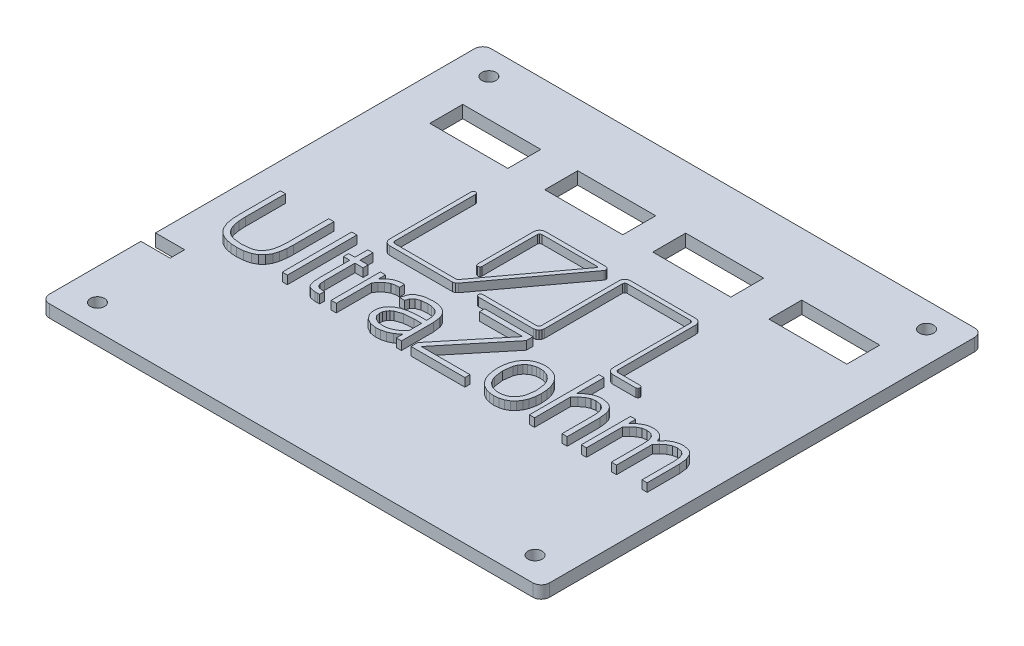
SolidWorks part; units mm, degrees
ref_plane "Ebene vorne" through (0, 0, 0) normal (0, 0, 1) x (1, 0, 0)
ref_plane "Ebene oben" through (0, 0, 0) normal (0, 1, 0) x (1, 0, 0)
ref_plane "Ebene rechts" through (0, 0, 0) normal (1, 0, 0) x (0, 0, -1)
sketch "Skizze1" plane through (0, 0, 0) normal (0, 1, 0) x (1, 0, 0)
  line L1 (-58, -53) -> (58, -53)
  line L2 (-60, -51) -> (-60, 51)
  line L3 (-58, 53) -> (58, 53)
  line L4 (60, -51) -> (60, 51)
  line L5 (-60, -53) -> (60, 53) construction
  line L6 (-60, 53) -> (60, -53) construction
  arc A0 (58, -53) -> (60, -51) centre (58, -51) ccw
  arc A1 (58, 53) -> (60, 51) centre (58, 51) cw
  arc A2 (-60, 51) -> (-58, 53) centre (-58, 51) cw
  arc A3 (-58, -53) -> (-60, -51) centre (-58, -51) cw
  point P0 (0, 0)
  dimension "D3" = 2
  dimension "D1" = 120
  dimension "D2" = 106
extrude "Aufsatz-Linear austragen1" add sketch "Skizze1" along normal blind 3
sketch "Skizze2" plane through (0, 3, 0) normal (0, 1, 0) x (1, 0, 0)
  line L1 (52.5, 46.97) -> (-52.5, 46.97) construction
  line L2 (52.5, 46.97) -> (52.5, -46.97) construction
  line L3 (52.5, -46.97) -> (-52.5, -46.97) construction
  line L4 (-52.5, 46.97) -> (-52.5, -46.97) construction
  line L5 (52.5, 46.97) -> (-52.5, -46.97) construction
  line L6 (52.5, -46.97) -> (-52.5, 46.97) construction
  circle A0 centre (-52.5, 46.97) radius 1.7
  circle A1 centre (52.5, 46.97) radius 1.7
  circle A2 centre (52.5, -46.97) radius 1.7
  circle A3 centre (-52.5, -46.97) radius 1.7
  point P0 (0, 0)
  dimension "D3" = 3.4
  dimension "D1" = 93.94
  dimension "D2" = 105
  dimension "D4" = 2
  dimension "D5" = 2
extrude "Schnitt-Linear austragen1" cut sketch "Skizze2" against normal blind 3
sketch "Skizze3" plane through (0, 3, 0) normal (0, 1, 0) x (1, 0, 0)
  line L0 (60, -51) -> (60, 51) construction
  line L1 (31.5, 30.13) -> (50.22, 30.13)
  line L2 (31.5, 30.13) -> (31.5, 38.03)
  line L3 (31.5, 38.03) -> (50.22, 38.03)
  line L4 (50.22, 30.13) -> (50.22, 38.03)
  line L5 (31.5, 30.13) -> (50.22, 38.03) construction
  line L6 (31.5, 38.03) -> (50.22, 30.13) construction
  line L7 (58, 53) -> (-58, 53) construction
  point P0 (40.86, 34.08)
  dimension "D1" = 9.78
  dimension "D2" = 18.72
  dimension "D3" = 7.9
  dimension "D4" = 14.97
extrude "Schnitt-Linear austragen2" cut sketch "Skizze3" against normal blind 3
pattern_linear "Lineares Muster1" count 2 spacing 27.85 along (-1, 0, 0) of "Schnitt-Linear austragen2"
pattern_linear "Lineares Muster2" count 2 spacing 53.76 along (-1, 0, 0) of "Schnitt-Linear austragen2"
pattern_linear "Lineares Muster3" count 2 spacing 81.35 along (-1, 0, 0) of "Schnitt-Linear austragen2"
sketch "Skizze4" plane through (0, 3, 0) normal (0, 1, 0) x (1, 0, 0)
  line L0 (-60, 51) -> (-60, -51) construction
  line L1 (-60, -29.05) -> (-53, -29.05)
  line L2 (-60, -29.05) -> (-60, -25.55)
  line L3 (-60, -25.55) -> (-53, -25.55)
  line L4 (-53, -29.05) -> (-53, -25.55)
  line L5 (-53, -27.3) -> (-60, -27.3) construction
  line L6 (-58, -53) -> (58, -53) construction
  dimension "D1" = 25.7
  dimension "D2" = 3.5
  dimension "D3" = 7
extrude "Schnitt-Linear austragen3" cut sketch "Skizze4" against normal blind 3
sketch "Skizze9" plane through (0, 3, 0) normal (0, 1, 0) x (1, 0, 0)
  line L0 (-12.1482, -2.1288) -> (-27.2801, -2.1288)
  line L1 (-27.2801, -2.1288) -> (-27.8105, -2.0208)
  line L2 (-27.8105, -2.0208) -> (-28.2435, -1.7282)
  line L3 (-28.2435, -1.7282) -> (-28.5353, -1.2947)
  line L4 (-28.5353, -1.2947) -> (-28.6423, -0.7641)
  line L5 (-28.6423, -0.7641) -> (-28.6423, 18.8843)
  line L6 (-28.6423, 18.8843) -> (-28.4902, 19.2514)
  line L7 (-28.4902, 19.2514) -> (-28.1231, 19.4035)
  line L8 (-28.1231, 19.4035) -> (-27.7576, 19.2505)
  line L9 (-27.7576, 19.2505) -> (-27.6065, 18.8843)
  line L10 (-27.6065, 18.8843) -> (-27.6065, -0.5614)
  line L11 (-27.6065, -0.5614) -> (-27.4542, -0.9276)
  line L12 (-27.4542, -0.9276) -> (-27.0873, -1.0781)
  line L13 (-27.0873, -1.0781) -> (-12.1482, -1.0781)
  line L14 (-12.1482, -1.0781) -> (-12.0395, -1.0212)
  line L15 (-12.0395, -1.0212) -> (2.1901, 18.2613)
  line L16 (2.1901, 18.2613) -> (2.2024, 18.4049)
  line L17 (2.2024, 18.4049) -> (2.0788, 18.4789)
  line L18 (2.0788, 18.4789) -> (-11.3374, 18.4789)
  line L19 (-11.3374, 18.4789) -> (-11.7045, 18.3268)
  line L20 (-11.7045, 18.3268) -> (-11.8565, 17.9597)
  line L21 (-11.8565, 17.9597) -> (-11.8565, 4.6399)
  line L22 (-11.8565, 4.6399) -> (-12.007, 4.273)
  line L23 (-12.007, 4.273) -> (-12.3732, 4.1208)
  line L24 (-12.3732, 4.1208) -> (-12.7403, 4.2728)
  line L25 (-12.7403, 4.2728) -> (-12.8924, 4.6399)
  line L26 (-12.8924, 4.6399) -> (-12.8924, 18.1427)
  line L27 (-12.8924, 18.1427) -> (-12.7853, 18.6729)
  line L28 (-12.7853, 18.6729) -> (-12.4934, 19.1059)
  line L29 (-12.4934, 19.1059) -> (-12.0604, 19.3978)
  line L30 (-12.0604, 19.3978) -> (-11.5302, 19.5048)
  line L31 (-11.5302, 19.5048) -> (3.0553, 19.5048)
  line L32 (3.0553, 19.5048) -> (3.4265, 19.4185)
  line L33 (3.4265, 19.4185) -> (3.6887, 19.1421)
  line L34 (3.6887, 19.1421) -> (3.7552, 18.7669)
  line L35 (3.7552, 18.7669) -> (3.6041, 18.4171)
  line L36 (3.6041, 18.4171) -> (-11.2113, -1.6343)
  line L37 (-11.2113, -1.6343) -> (-11.6241, -1.987)
  line L38 (-11.6241, -1.987) -> (-12.1482, -2.1288)
  line L39 (-12.1482, -2.1288) -> (-12.1482, -2.1288)
  line L40 (31.8284, -2.1288) -> (26.281, -2.1288)
  line L41 (26.281, -2.1288) -> (25.7506, -2.0208)
  line L42 (25.7506, -2.0208) -> (25.3176, -1.7282)
  line L43 (25.3176, -1.7282) -> (25.0258, -1.2947)
  line L44 (25.0258, -1.2947) -> (24.9188, -0.7641)
  line L45 (24.9188, -0.7641) -> (24.9188, 17.9523)
  line L46 (24.9188, 17.9523) -> (24.7676, 18.3185)
  line L47 (24.7676, 18.3185) -> (24.4021, 18.4715)
  line L48 (24.4021, 18.4715) -> (9.1096, 18.4715)
  line L49 (9.1096, 18.4715) -> (8.7441, 18.3185)
  line L50 (8.7441, 18.3185) -> (8.5929, 17.9523)
  line L51 (8.5929, 17.9523) -> (8.5929, -0.7518)
  line L52 (8.5929, -0.7518) -> (8.4931, -1.2767)
  line L53 (8.4931, -1.2767) -> (8.1994, -1.723)
  line L54 (8.1994, -1.723) -> (7.7568, -2.0223)
  line L55 (7.7568, -2.0223) -> (7.2332, -2.1288)
  line L56 (7.2332, -2.1288) -> (-5.9605, -2.1288)
  line L57 (-5.9605, -2.1288) -> (-6.3276, -1.9767)
  line L58 (-6.3276, -1.9767) -> (-6.4797, -1.6096)
  line L59 (-6.4797, -1.6096) -> (-6.3276, -1.2425)
  line L60 (-6.3276, -1.2425) -> (-5.9605, -1.0905)
  line L61 (-5.9605, -1.0905) -> (7.0379, -1.0905)
  line L62 (7.0379, -1.0905) -> (7.4049, -0.94)
  line L63 (7.4049, -0.94) -> (7.5571, -0.5738)
  line L64 (7.5571, -0.5738) -> (7.5571, 18.1427)
  line L65 (7.5571, 18.1427) -> (7.6608, 18.664)
  line L66 (7.6608, 18.664) -> (7.956, 19.1059)
  line L67 (7.956, 19.1059) -> (8.3979, 19.4011)
  line L68 (8.3979, 19.4011) -> (8.9192, 19.5048)
  line L69 (8.9192, 19.5048) -> (24.5925, 19.5048)
  line L70 (24.5925, 19.5048) -> (25.1138, 19.4011)
  line L71 (25.1138, 19.4011) -> (25.5557, 19.1059)
  line L72 (25.5557, 19.1059) -> (25.851, 18.664)
  line L73 (25.851, 18.664) -> (25.9546, 18.1427)
  line L74 (25.9546, 18.1427) -> (25.9546, -0.5639)
  line L75 (25.9546, -0.5639) -> (26.1068, -0.9301)
  line L76 (26.1068, -0.9301) -> (26.4738, -1.0806)
  line L77 (26.4738, -1.0806) -> (31.8284, -1.0806)
  line L78 (31.8284, -1.0806) -> (32.1939, -1.2335)
  line L79 (32.1939, -1.2335) -> (32.3451, -1.5997)
  line L80 (32.3451, -1.5997) -> (32.1974, -1.9723)
  line L81 (32.1974, -1.9723) -> (31.8284, -2.1288)
  line L82 (-45.3538, -20.7933) -> (-46.6503, -20.7279)
  line L83 (-46.6503, -20.7279) -> (-47.9249, -20.4818)
  line L84 (-47.9249, -20.4818) -> (-48.8507, -20.1396)
  line L85 (-48.8507, -20.1396) -> (-49.6998, -19.6364)
  line L86 (-49.6998, -19.6364) -> (-50.323, -19.0688)
  line L87 (-50.323, -19.0688) -> (-50.8197, -18.3879)
  line L88 (-50.8197, -18.3879) -> (-51.4501, -16.8651)
  line L89 (-51.4501, -16.8651) -> (-51.7196, -15.189)
  line L90 (-51.7196, -15.189) -> (-51.774, -13.4981)
  line L91 (-51.774, -13.4981) -> (-51.774, -3.8098)
  line L92 (-51.774, -3.8098) -> (-50.5379, -3.8098)
  line L93 (-50.5379, -3.8098) -> (-50.5379, -13.4511)
  line L94 (-50.5379, -13.4511) -> (-50.4708, -15.013)
  line L95 (-50.4708, -15.013) -> (-50.1918, -16.5511)
  line L96 (-50.1918, -16.5511) -> (-49.8031, -17.5485)
  line L97 (-49.8031, -17.5485) -> (-49.1782, -18.4176)
  line L98 (-49.1782, -18.4176) -> (-48.4265, -18.987)
  line L99 (-48.4265, -18.987) -> (-47.5491, -19.3323)
  line L100 (-47.5491, -19.3323) -> (-45.3464, -19.5795)
  line L101 (-45.3464, -19.5795) -> (-43.1215, -19.3323)
  line L102 (-43.1215, -19.3323) -> (-42.2409, -18.988)
  line L103 (-42.2409, -18.988) -> (-41.4924, -18.4102)
  line L104 (-41.4924, -18.4102) -> (-40.883, -17.5379)
  line L105 (-40.883, -17.5379) -> (-40.5035, -16.5437)
  line L106 (-40.5035, -16.5437) -> (-40.2315, -15.0087)
  line L107 (-40.2315, -15.0087) -> (-40.1673, -13.4511)
  line L108 (-40.1673, -13.4511) -> (-40.1673, -3.8098)
  line L109 (-40.1673, -3.8098) -> (-38.9313, -3.8098)
  line L110 (-38.9313, -3.8098) -> (-38.9313, -13.5005)
  line L111 (-38.9313, -13.5005) -> (-38.9957, -15.0459)
  line L112 (-38.9957, -15.0459) -> (-39.223, -16.5759)
  line L113 (-39.223, -16.5759) -> (-39.6001, -17.7802)
  line L114 (-39.6001, -17.7802) -> (-40.2365, -18.87)
  line L115 (-40.2365, -18.87) -> (-41.1247, -19.7201)
  line L116 (-41.1247, -19.7201) -> (-42.2093, -20.2989)
  line L117 (-42.2093, -20.2989) -> (-43.7585, -20.6926)
  line L118 (-43.7585, -20.6926) -> (-45.3538, -20.7933)
  line L119 (-33.4036, -20.4892) -> (-34.6396, -20.4892)
  line L120 (-34.6396, -20.4892) -> (-34.6396, -3.8098)
  line L121 (-34.6396, -3.8098) -> (-33.4036, -3.8098)
  line L122 (-33.4036, -3.8098) -> (-33.4036, -20.4892)
  line L123 (-25.5398, -20.5955) -> (-26.0614, -20.6425)
  line L124 (-26.0614, -20.6425) -> (-26.583, -20.6573)
  line L125 (-26.583, -20.6573) -> (-27.866, -20.4349)
  line L126 (-27.866, -20.4349) -> (-28.2913, -20.1646)
  line L127 (-28.2913, -20.1646) -> (-28.6077, -19.7723)
  line L128 (-28.6077, -19.7723) -> (-28.9389, -18.6698)
  line L129 (-28.9389, -18.6698) -> (-29.0156, -17.1222)
  line L130 (-29.0156, -17.1222) -> (-29.0156, -9.9036)
  line L131 (-29.0156, -9.9036) -> (-30.5359, -9.9036)
  line L132 (-30.5359, -9.9036) -> (-30.5359, -8.6848)
  line L133 (-30.5359, -8.6848) -> (-29.0156, -8.6848)
  line L134 (-29.0156, -8.6848) -> (-29.0156, -5.5897)
  line L135 (-29.0156, -5.5897) -> (-27.7795, -5.5897)
  line L136 (-27.7795, -5.5897) -> (-27.7795, -8.6824)
  line L137 (-27.7795, -8.6824) -> (-25.829, -8.6824)
  line L138 (-25.829, -8.6824) -> (-25.829, -9.9011)
  line L139 (-25.829, -9.9011) -> (-27.7795, -9.9011)
  line L140 (-27.7795, -9.9011) -> (-27.7795, -17.226)
  line L141 (-27.7795, -17.226) -> (-27.6707, -18.3929)
  line L142 (-27.6707, -18.3929) -> (-27.3494, -19.0628)
  line L143 (-27.3494, -19.0628) -> (-26.8203, -19.3669)
  line L144 (-26.8203, -19.3669) -> (-26.1059, -19.4361)
  line L145 (-26.1059, -19.4361) -> (-25.8142, -19.4361)
  line L146 (-25.8142, -19.4361) -> (-25.5373, -19.4213)
  line L147 (-25.5373, -19.4213) -> (-25.5398, -20.5955)
  line L148 (-17.4139, -9.6292) -> (-17.7822, -9.5995)
  line L149 (-17.7822, -9.5995) -> (-18.2297, -9.5995)
  line L150 (-18.2297, -9.5995) -> (-19.2457, -9.8121)
  line L151 (-19.2457, -9.8121) -> (-20.1827, -10.3684)
  line L152 (-20.1827, -10.3684) -> (-21.0108, -11.1446)
  line L153 (-21.0108, -11.1446) -> (-21.6709, -12.0346)
  line L154 (-21.6709, -12.0346) -> (-21.6709, -20.4892)
  line L155 (-21.6709, -20.4892) -> (-22.9069, -20.4892)
  line L156 (-22.9069, -20.4892) -> (-22.9069, -8.6848)
  line L157 (-22.9069, -8.6848) -> (-21.6709, -8.6848)
  line L158 (-21.6709, -8.6848) -> (-21.6709, -10.314)
  line L159 (-21.6709, -10.314) -> (-20.6351, -9.3251)
  line L160 (-20.6351, -9.3251) -> (-19.6462, -8.7293)
  line L161 (-19.6462, -8.7293) -> (-18.7167, -8.4475)
  line L162 (-18.7167, -8.4475) -> (-17.9034, -8.3808)
  line L163 (-17.9034, -8.3808) -> (-17.6734, -8.3808)
  line L164 (-17.6734, -8.3808) -> (-17.4262, -8.403)
  line L165 (-17.4262, -8.403) -> (-17.4139, -9.6292)
  line L166 (-7.2782, -18.9664) -> (-8.5142, -19.8712)
  line L167 (-8.5142, -19.8712) -> (-9.6885, -20.4349)
  line L168 (-9.6885, -20.4349) -> (-10.8331, -20.7167)
  line L169 (-10.8331, -20.7167) -> (-11.9851, -20.7933)
  line L170 (-11.9851, -20.7933) -> (-13.4436, -20.5585)
  line L171 (-13.4436, -20.5585) -> (-14.6105, -19.8885)
  line L172 (-14.6105, -19.8885) -> (-15.3867, -18.8354)
  line L173 (-15.3867, -18.8354) -> (-15.6038, -18.17)
  line L174 (-15.6038, -18.17) -> (-15.671, -17.4732)
  line L175 (-15.671, -17.4732) -> (-15.5689, -16.5293)
  line L176 (-15.5689, -16.5293) -> (-15.2283, -15.6602)
  line L177 (-15.2283, -15.6602) -> (-14.6733, -14.9096)
  line L178 (-14.6733, -14.9096) -> (-13.9282, -14.3213)
  line L179 (-13.9282, -14.3213) -> (-12.9477, -13.8281)
  line L180 (-12.9477, -13.8281) -> (-11.749, -13.4758)
  line L181 (-11.749, -13.4758) -> (-10.3322, -13.2645)
  line L182 (-10.3322, -13.2645) -> (-8.6972, -13.194)
  line L183 (-8.6972, -13.194) -> (-7.2856, -13.194)
  line L184 (-7.2856, -13.194) -> (-7.377, -11.7626)
  line L185 (-7.377, -11.7626) -> (-7.8072, -10.6279)
  line L186 (-7.8072, -10.6279) -> (-8.2471, -10.1794)
  line L187 (-8.2471, -10.1794) -> (-8.796, -9.8739)
  line L188 (-8.796, -9.8739) -> (-9.6815, -9.6506)
  line L189 (-9.6815, -9.6506) -> (-10.5933, -9.5995)
  line L190 (-10.5933, -9.5995) -> (-12.0562, -9.7287)
  line L191 (-12.0562, -9.7287) -> (-13.1025, -10.1162)
  line L192 (-13.1025, -10.1162) -> (-13.7798, -10.7859)
  line L193 (-13.7798, -10.7859) -> (-14.0913, -11.686)
  line L194 (-14.0913, -11.686) -> (-15.3051, -11.686)
  line L195 (-15.3051, -11.686) -> (-14.8824, -10.225)
  line L196 (-14.8824, -10.225) -> (-14.4931, -9.6558)
  line L197 (-14.4931, -9.6558) -> (-13.985, -9.1941)
  line L198 (-13.985, -9.1941) -> (-12.5728, -8.5829)
  line L199 (-12.5728, -8.5829) -> (-10.6056, -8.3808)
  line L200 (-10.6056, -8.3808) -> (-9.5373, -8.4446)
  line L201 (-9.5373, -8.4446) -> (-8.4944, -8.6848)
  line L202 (-8.4944, -8.6848) -> (-7.7351, -9.0379)
  line L203 (-7.7351, -9.0379) -> (-7.0804, -9.56)
  line L204 (-7.0804, -9.56) -> (-6.6018, -10.206)
  line L205 (-6.6018, -10.206) -> (-6.2893, -10.9468)
  line L206 (-6.2893, -10.9468) -> (-6.0421, -12.7811)
  line L207 (-6.0421, -12.7811) -> (-6.0421, -20.4892)
  line L208 (-6.0421, -20.4892) -> (-7.2782, -20.4892)
  line L209 (-7.2782, -20.4892) -> (-7.2782, -18.9664)
  line L210 (-7.2782, -14.4128) -> (-9.1347, -14.4128)
  line L211 (-9.1347, -14.4128) -> (-11.469, -14.6031)
  line L212 (-11.469, -14.6031) -> (-13.1223, -15.1742)
  line L213 (-13.1223, -15.1742) -> (-13.6752, -15.5602)
  line L214 (-13.6752, -15.5602) -> (-14.0918, -16.0743)
  line L215 (-14.0918, -16.0743) -> (-14.3519, -16.6829)
  line L216 (-14.3519, -16.6829) -> (-14.435, -17.3521)
  line L217 (-14.435, -17.3521) -> (-14.2315, -18.2779)
  line L218 (-14.2315, -18.2779) -> (-13.6043, -18.9887)
  line L219 (-13.6043, -18.9887) -> (-12.6223, -19.4281)
  line L220 (-12.6223, -19.4281) -> (-11.3324, -19.5746)
  line L221 (-11.3324, -19.5746) -> (-10.1112, -19.3842)
  line L222 (-10.1112, -19.3842) -> (-8.9963, -18.8898)
  line L223 (-8.9963, -18.8898) -> (-8.0371, -18.2124)
  line L224 (-8.0371, -18.2124) -> (-7.2782, -17.4881)
  line L225 (-7.2782, -17.4881) -> (-7.2782, -14.4128)
  line L226 (9.1862, -20.4892) -> (-3.748, -20.4892)
  line L227 (-3.748, -20.4892) -> (-3.748, -18.8749)
  line L228 (-3.748, -18.8749) -> (7.604, -5.031)
  line L229 (7.604, -5.031) -> (-2.7492, -5.031)
  line L230 (-2.7492, -5.031) -> (-2.7492, -3.8098)
  line L231 (-2.7492, -3.8098) -> (8.8698, -3.8098)
  line L232 (8.8698, -3.8098) -> (8.8698, -5.4414)
  line L233 (8.8698, -5.4414) -> (-2.502, -19.2705)
  line L234 (-2.502, -19.2705) -> (9.1862, -19.2705)
  line L235 (9.1862, -19.2705) -> (9.1862, -20.4892)
  line L236 (16.3801, -8.3808) -> (17.5017, -8.4803)
  line L237 (17.5017, -8.4803) -> (18.5803, -8.8035)
  line L238 (18.5803, -8.8035) -> (19.4876, -9.3161)
  line L239 (19.4876, -9.3161) -> (20.2539, -10.0223)
  line L240 (20.2539, -10.0223) -> (20.8879, -10.9407)
  line L241 (20.8879, -10.9407) -> (21.3243, -11.9678)
  line L242 (21.3243, -11.9678) -> (21.6052, -13.2655)
  line L243 (21.6052, -13.2655) -> (21.6989, -14.5833)
  line L244 (21.6989, -14.5833) -> (21.6052, -15.9011)
  line L245 (21.6052, -15.9011) -> (21.3243, -17.1988)
  line L246 (21.3243, -17.1988) -> (20.8899, -18.2313)
  line L247 (20.8899, -18.2313) -> (20.2589, -19.1568)
  line L248 (20.2589, -19.1568) -> (19.4908, -19.8624)
  line L249 (19.4908, -19.8624) -> (18.5828, -20.3755)
  line L250 (18.5828, -20.3755) -> (17.5091, -20.6858)
  line L251 (17.5091, -20.6858) -> (16.4061, -20.7892)
  line L252 (16.4061, -20.7892) -> (15.303, -20.6858)
  line L253 (15.303, -20.6858) -> (14.2293, -20.3755)
  line L254 (14.2293, -20.3755) -> (13.3252, -19.8676)
  line L255 (13.3252, -19.8676) -> (12.5631, -19.1642)
  line L256 (12.5631, -19.1642) -> (11.928, -18.2388)
  line L257 (11.928, -18.2388) -> (11.4878, -17.2063)
  line L258 (11.4878, -17.2063) -> (11.2031, -15.9013)
  line L259 (11.2031, -15.9013) -> (11.1082, -14.5759)
  line L260 (11.1082, -14.5759) -> (11.2031, -13.2505)
  line L261 (11.2031, -13.2505) -> (11.4878, -11.9456)
  line L262 (11.4878, -11.9456) -> (11.9228, -10.9197)
  line L263 (11.9228, -10.9197) -> (12.5557, -10.0025)
  line L264 (12.5557, -10.0025) -> (13.3229, -9.3006)
  line L265 (13.3229, -9.3006) -> (14.2293, -8.7911)
  line L266 (14.2293, -8.7911) -> (15.2841, -8.4779)
  line L267 (15.2841, -8.4779) -> (16.3801, -8.3808)
  line L268 (16.3801, -19.5746) -> (17.2214, -19.5013)
  line L269 (17.2214, -19.5013) -> (18.0315, -19.2631)
  line L270 (18.0315, -19.2631) -> (18.7297, -18.868)
  line L271 (18.7297, -18.868) -> (19.3145, -18.3187)
  line L272 (19.3145, -18.3187) -> (19.8115, -17.576)
  line L273 (19.8115, -17.576) -> (20.1501, -16.7489)
  line L274 (20.1501, -16.7489) -> (20.4517, -14.571)
  line L275 (20.4517, -14.571) -> (20.1501, -12.393)
  line L276 (20.1501, -12.393) -> (19.8125, -11.5736)
  line L277 (19.8125, -11.5736) -> (19.3145, -10.8405)
  line L278 (19.3145, -10.8405) -> (18.7274, -10.3006)
  line L279 (18.7274, -10.3006) -> (18.0315, -9.911)
  line L280 (18.0315, -9.911) -> (17.213, -9.6774)
  line L281 (17.213, -9.6774) -> (16.3727, -9.5996)
  line L282 (16.3727, -9.5996) -> (15.5323, -9.6774)
  line L283 (15.5323, -9.6774) -> (14.7139, -9.911)
  line L284 (14.7139, -9.911) -> (14.0179, -10.3006)
  line L285 (14.0179, -10.3006) -> (13.4308, -10.8405)
  line L286 (13.4308, -10.8405) -> (12.9351, -11.5732)
  line L287 (12.9351, -11.5732) -> (12.6027, -12.393)
  line L288 (12.6027, -12.393) -> (12.311, -14.571)
  line L289 (12.311, -14.571) -> (12.6027, -16.7489)
  line L290 (12.6027, -16.7489) -> (12.9362, -17.5763)
  line L291 (12.9362, -17.5763) -> (13.4308, -18.3187)
  line L292 (13.4308, -18.3187) -> (14.0156, -18.868)
  line L293 (14.0156, -18.868) -> (14.7139, -19.2631)
  line L294 (14.7139, -19.2631) -> (15.5314, -19.502)
  line L295 (15.5314, -19.502) -> (16.3801, -19.5746)
  line L296 (25.9052, -10.4376) -> (27.0473, -9.3696)
  line L297 (27.0473, -9.3696) -> (28.14, -8.7466)
  line L298 (28.14, -8.7466) -> (29.1536, -8.4574)
  line L299 (29.1536, -8.4574) -> (30.0658, -8.3808)
  line L300 (30.0658, -8.3808) -> (31.6719, -8.6491)
  line L301 (31.6719, -8.6491) -> (32.3029, -8.9846)
  line L302 (32.3029, -8.9846) -> (32.8191, -9.4543)
  line L303 (32.8191, -9.4543) -> (33.2206, -10.0581)
  line L304 (33.2206, -10.0581) -> (33.5075, -10.7962)
  line L305 (33.5075, -10.7962) -> (33.7369, -12.6748)
  line L306 (33.7369, -12.6748) -> (33.7369, -20.4892)
  line L307 (33.7369, -20.4892) -> (32.5008, -20.4892)
  line L308 (32.5008, -20.4892) -> (32.5008, -12.7811)
  line L309 (32.5008, -12.7811) -> (32.355, -11.3572)
  line L310 (32.355, -11.3572) -> (31.8803, -10.3684)
  line L311 (31.8803, -10.3684) -> (31.02, -9.7899)
  line L312 (31.02, -9.7899) -> (29.7222, -9.5995)
  line L313 (29.7222, -9.5995) -> (28.7073, -9.7542)
  line L314 (28.7073, -9.7542) -> (27.7791, -10.1928)
  line L315 (27.7791, -10.1928) -> (26.7794, -10.9647)
  line L316 (26.7794, -10.9647) -> (25.8978, -11.8689)
  line L317 (25.8978, -11.8689) -> (25.8978, -20.4892)
  line L318 (25.8978, -20.4892) -> (24.6617, -20.4892)
  line L319 (24.6617, -20.4892) -> (24.6617, -3.8098)
  line L320 (24.6617, -3.8098) -> (25.8978, -3.8098)
  line L321 (25.8978, -3.8098) -> (25.9052, -10.4376)
  line L322 (52.9181, -20.4892) -> (51.6821, -20.4892)
  line L323 (51.6821, -20.4892) -> (51.6821, -12.7811)
  line L324 (51.6821, -12.7811) -> (51.5498, -11.3269)
  line L325 (51.5498, -11.3269) -> (51.153, -10.3461)
  line L326 (51.153, -10.3461) -> (50.4163, -9.7899)
  line L327 (50.4163, -9.7899) -> (49.2866, -9.6045)
  line L328 (49.2866, -9.6045) -> (48.2857, -9.7642)
  line L329 (48.2857, -9.7642) -> (47.3731, -10.2052)
  line L330 (47.3731, -10.2052) -> (46.4025, -10.9817)
  line L331 (46.4025, -10.9817) -> (45.5685, -11.9035)
  line L332 (45.5685, -11.9035) -> (45.5685, -20.4942)
  line L333 (45.5685, -20.4942) -> (44.3324, -20.4942)
  line L334 (44.3324, -20.4942) -> (44.3324, -12.7811)
  line L335 (44.3324, -12.7811) -> (44.2187, -11.335)
  line L336 (44.2187, -11.335) -> (43.8256, -10.3461)
  line L337 (43.8256, -10.3461) -> (43.084, -9.7825)
  line L338 (43.084, -9.7825) -> (41.9715, -9.5995)
  line L339 (41.9715, -9.5995) -> (41.003, -9.7574)
  line L340 (41.003, -9.7574) -> (40.1273, -10.2002)
  line L341 (40.1273, -10.2002) -> (39.1842, -10.9864)
  line L342 (39.1842, -10.9864) -> (38.3622, -11.8986)
  line L343 (38.3622, -11.8986) -> (38.3622, -20.4892)
  line L344 (38.3622, -20.4892) -> (37.1262, -20.4892)
  line L345 (37.1262, -20.4892) -> (37.1262, -8.6848)
  line L346 (37.1262, -8.6848) -> (38.3622, -8.6848)
  line L347 (38.3622, -8.6848) -> (38.3622, -10.4376)
  line L348 (38.3622, -10.4376) -> (39.5217, -9.3474)
  line L349 (39.5217, -9.3474) -> (40.5501, -8.7293)
  line L350 (40.5501, -8.7293) -> (41.4722, -8.4475)
  line L351 (41.4722, -8.4475) -> (42.3078, -8.3808)
  line L352 (42.3078, -8.3808) -> (43.3361, -8.4994)
  line L353 (43.3361, -8.4994) -> (44.2855, -8.9123)
  line L354 (44.2855, -8.9123) -> (45.0183, -9.6259)
  line L355 (45.0183, -9.6259) -> (45.4696, -10.5439)
  line L356 (45.4696, -10.5439) -> (46.4436, -9.4833)
  line L357 (46.4436, -9.4833) -> (47.4893, -8.8208)
  line L358 (47.4893, -8.8208) -> (48.5573, -8.4796)
  line L359 (48.5573, -8.4796) -> (49.6005, -8.3808)
  line L360 (49.6005, -8.3808) -> (51.0464, -8.6491)
  line L361 (51.0464, -8.6491) -> (51.6143, -8.9846)
  line L362 (51.6143, -8.9846) -> (52.0788, -9.4543)
  line L363 (52.0788, -9.4543) -> (52.6978, -10.7962)
  line L364 (52.6978, -10.7962) -> (52.9033, -12.6748)
  line L365 (52.9033, -12.6748) -> (52.9181, -20.4892)
extrude "Aufsatz-Linear austragen2" add sketch "Skizze9" along normal blind 2 contours L118 L117 L116 L115 L114 L113 L112 L111 L110 L109 L108 L107 L106 L105 L104 L103 L102 L101 L100 L99 L98 L97 L96 L95 L94 L93 L92 L91 L90 L89 L88 L87 L86 L85 L84 L83 L82 | L122 L121 L120 L119 | L147 L146 L145 L144 L143 L142 L141 L140 L139 L138 L137 L136 L135 L134 L133 L132 L131 L130 L129 L128 L127 L126 L125 L124 L123 | L165 L164 L163 L162 L161 L160 L159 L158 L157 L156 L155 L154 L153 L152 L151 L150 L149 L148 | L224 L225 L210 L211 L212 L213 L214 L215 L216 L217 L218 L219 L220 L221 L222 L223 | L235 L234 L233 L232 L231 L230 L229 L228 L227 L226 | L267 L266 L265 L264 L263 L262 L261 L260 L259 L258 L257 L256 L255 L254 L253 L252 L251 L250 L249 L248 L247 L246 L245 L244 L243 L242 L241 L240 L239 L238 L237 L236 L295 L294 L293 L292 L291 L290 L289 L288 L287 L286 L285 L284 L283 L282 L281 L280 L279 L278 | L321 L320 L319 L318 L317 L316 L315 L314 L313 L312 L311 L310 L309 L308 L307 L306 L305 L304 L303 L302 L301 L300 L299 L298 L297 L296 | L365 L364 L363 L362 L361 L360 L359 L358 L357 L356 L355 L354 L353 L352 L351 L350 L349 L348 L347 L346 L345 L344 L343 L342 L341 L340 L339 L338 L337 L336 L335 L334 L333 L332 L331 L330 L329 L328 L327 L326 L325 L324 L323 L322 | L38 L37 L36 L35 L34 L33 L32 L31 L30 L29 L28 L27 L26 L25 L24 L23 L22 L21 L20 L19 L18 L17 L16 L15 L14 L13 L12 L11 L10 L9 L8 L7 L6 L5 L4 L3 L2 L1 L0 | L81 L80 L79 L78 L77 L76 L75 L74 L73 L72 L71 L70 L69 L68 L67 L66 L65 L64 L63 L62 L61 L60 L59 L58 L57 L56 L55 L54 L53 L52 L51 L50 L49 L48 L47 L46 L45 L44 L43 L42 L41 L40 | L191 L192 L193 L194 L195 L196 L197 L198 L199 L200 L201 L202 L203 L204 L205 L206 L207 L208 L209 L166 L167 L168 L169 L170 L171 L172 L173 L174 L175 L176 L177 L178 L179 L180 L181 L182 L183 L184 L185 L186 L187 L188 L189 L190
